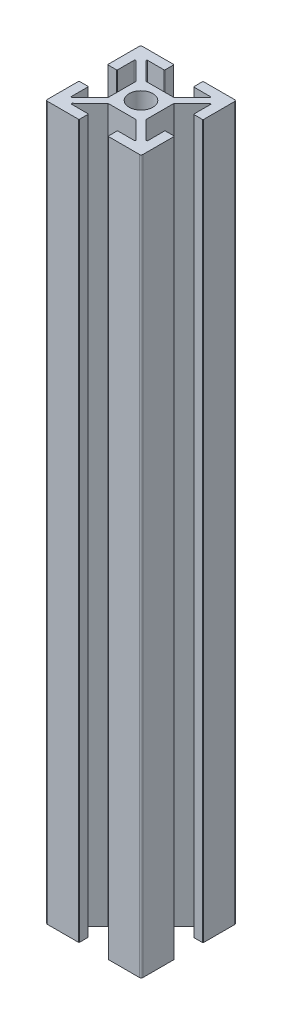
SolidWorks part; units mm, degrees
ref_plane "Front Plane" through (0, 0, 0) normal (0, 0, 1) x (1, 0, 0)
ref_plane "Top Plane" through (0, 0, 0) normal (0, 1, 0) x (1, 0, 0)
ref_plane "Right Plane" through (0, 0, 0) normal (1, 0, 0) x (0, 0, -1)
sketch "Sketch1" plane through (0, 0, 0) normal (0, 1, 0) x (1, 0, 0)
  line L0 (-9.8963, 3) -> (-8.1963, 3)
  line L3 (-3.1963, 10) -> (-9.6963, 10)
  line L4 (-10.0463, 3.15) -> (-10.0463, 9.65)
  line L7 (2.9332, 4) -> (-2.9332, 4)
  line L8 (-4, -2.9454) -> (-4, 2.9454)
  line L9 (-8.0463, 3.15) -> (-8.0463, 6.5862)
  line L10 (-6.6144, 8) -> (-3.1963, 8)
  line L11 (-3.0463, 8.15) -> (-3.0463, 9.85)
  line L12 (-8.0463, 8) -> (-4, 4) construction
  line L13 (-7.7908, 6.6929) -> (-4, 2.9454)
  line L14 (-6.7198, 7.7433) -> (-2.9332, 4)
  line L15 (8.0463, 8) -> (4, 4) construction
  line L22 (0, 0) -> (0, 11.6886) construction
  line L25 (0, 0) -> (-14.9841, 0) construction
  line L27 (6.7198, 7.7433) -> (2.9332, 4)
  line L28 (7.7908, 6.6929) -> (4, 2.9454)
  line L46 (3.0463, 8.15) -> (3.0463, 9.85)
  line L47 (6.6144, 8) -> (3.1963, 8)
  line L48 (8.0463, 3.15) -> (8.0463, 6.5862)
  line L49 (4, -2.9454) -> (4, 2.9454)
  line L50 (10.0463, 3.15) -> (10.0463, 9.65)
  line L51 (3.1963, 10) -> (9.6963, 10)
  line L52 (9.8963, 3) -> (8.1963, 3)
  line L53 (8.0463, -8) -> (4, -4) construction
  line L54 (-8.0463, -8) -> (-4, -4) construction
  line L55 (9.8963, -3) -> (8.1963, -3)
  line L56 (3.1963, -10) -> (9.6963, -10)
  line L57 (10.0463, -3.15) -> (10.0463, -9.65)
  line L58 (8.0463, -3.15) -> (8.0463, -6.5862)
  line L59 (6.6144, -8) -> (3.1963, -8)
  line L60 (3.0463, -8.15) -> (3.0463, -9.85)
  line L61 (7.7908, -6.6929) -> (4, -2.9454)
  line L62 (6.7198, -7.7433) -> (2.9332, -4)
  line L63 (-6.7198, -7.7433) -> (-2.9332, -4)
  line L64 (-7.7908, -6.6929) -> (-4, -2.9454)
  line L65 (-3.0463, -8.15) -> (-3.0463, -9.85)
  line L66 (-6.6144, -8) -> (-3.1963, -8)
  line L67 (-8.0463, -3.15) -> (-8.0463, -6.5862)
  line L68 (2.9332, -4) -> (-2.9332, -4)
  line L69 (-10.0463, -3.15) -> (-10.0463, -9.65)
  line L70 (-3.1963, -10) -> (-9.6963, -10)
  line L71 (-9.8963, -3) -> (-8.1963, -3)
  circle A0 centre (0, 0) radius 2.5
  arc A1 (-10.0463, 9.65) -> (-9.6963, 10) centre (-9.6963, 9.65) cw
  arc A2 (-9.8963, 3) -> (-10.0463, 3.15) centre (-9.8963, 3.15) cw
  arc A3 (-8.1963, 3) -> (-8.0463, 3.15) centre (-8.1963, 3.15) ccw
  arc A4 (-3.1963, 10) -> (-3.0463, 9.85) centre (-3.1963, 9.85) cw
  arc A5 (-3.1963, 8) -> (-3.0463, 8.15) centre (-3.1963, 8.15) ccw
  arc A6 (-6.7198, 7.7433) -> (-6.6144, 8) centre (-6.6144, 7.85) cw
  arc A7 (-7.7908, 6.6929) -> (-8.0463, 6.5862) centre (-7.8963, 6.5862) ccw
  arc A8 (7.7908, 6.6929) -> (8.0463, 6.5862) centre (7.8963, 6.5862) cw
  arc A9 (6.7198, 7.7433) -> (6.6144, 8) centre (6.6144, 7.85) ccw
  arc A10 (3.1963, 8) -> (3.0463, 8.15) centre (3.1963, 8.15) cw
  arc A11 (3.1963, 10) -> (3.0463, 9.85) centre (3.1963, 9.85) ccw
  arc A12 (8.1963, 3) -> (8.0463, 3.15) centre (8.1963, 3.15) cw
  arc A13 (9.8963, 3) -> (10.0463, 3.15) centre (9.8963, 3.15) ccw
  arc A14 (10.0463, 9.65) -> (9.6963, 10) centre (9.6963, 9.65) ccw
  arc A15 (10.0463, -9.65) -> (9.6963, -10) centre (9.6963, -9.65) cw
  arc A16 (9.8963, -3) -> (10.0463, -3.15) centre (9.8963, -3.15) cw
  arc A17 (8.1963, -3) -> (8.0463, -3.15) centre (8.1963, -3.15) ccw
  arc A18 (3.1963, -10) -> (3.0463, -9.85) centre (3.1963, -9.85) cw
  arc A19 (3.1963, -8) -> (3.0463, -8.15) centre (3.1963, -8.15) ccw
  arc A20 (6.7198, -7.7433) -> (6.6144, -8) centre (6.6144, -7.85) cw
  arc A21 (7.7908, -6.6929) -> (8.0463, -6.5862) centre (7.8963, -6.5862) ccw
  arc A22 (-7.7908, -6.6929) -> (-8.0463, -6.5862) centre (-7.8963, -6.5862) cw
  arc A23 (-6.7198, -7.7433) -> (-6.6144, -8) centre (-6.6144, -7.85) ccw
  arc A24 (-3.1963, -8) -> (-3.0463, -8.15) centre (-3.1963, -8.15) cw
  arc A25 (-3.1963, -10) -> (-3.0463, -9.85) centre (-3.1963, -9.85) ccw
  arc A26 (-8.1963, -3) -> (-8.0463, -3.15) centre (-8.1963, -3.15) cw
  arc A27 (-9.8963, -3) -> (-10.0463, -3.15) centre (-9.8963, -3.15) ccw
  arc A28 (-10.0463, -9.65) -> (-9.6963, -10) centre (-9.6963, -9.65) ccw
  point P8 (-10.0463, 10)
  point P27 (-10.0463, 3)
  point P30 (3.0463, 8)
  point P31 (10.0463, -10)
  point P50 (4, 0)
  point P55 (-8.0463, 3)
  point P58 (-3.0463, 10)
  point P61 (-3.0463, 8)
  point P63 (0, 4)
  point P65 (3.0463, 10)
  point P66 (8.0463, 3)
  point P67 (10.0463, 3)
  point P68 (10.0463, 10)
  point P118 (-4, 0)
  point P119 (10.0463, -3)
  point P120 (8.0463, -3)
  point P121 (3.0463, -10)
  point P122 (0, -4)
  point P123 (-3.0463, -8)
  point P124 (-3.0463, -10)
  point P125 (-8.0463, -3)
  point P126 (3.0463, -8)
  point P127 (-10.0463, -3)
  point P128 (-10.0463, -10)
  dimension "D2" = 0.35
  dimension "D3" = 0.15
  dimension "D4" = 0.15
  dimension "D5" = 0.15
  dimension "D12" = 0.15
  dimension "D13" = 0.15
  dimension "D14" = 0.15
  dimension "D6" = 2
  dimension "D7" = 7
  dimension "D8" = 7
  dimension "D9" = 2
  dimension "D10" = 0.75
  dimension "D11" = 0.75
extrude "Boss-Extrude2" add sketch "Sketch1" along normal blind 150
